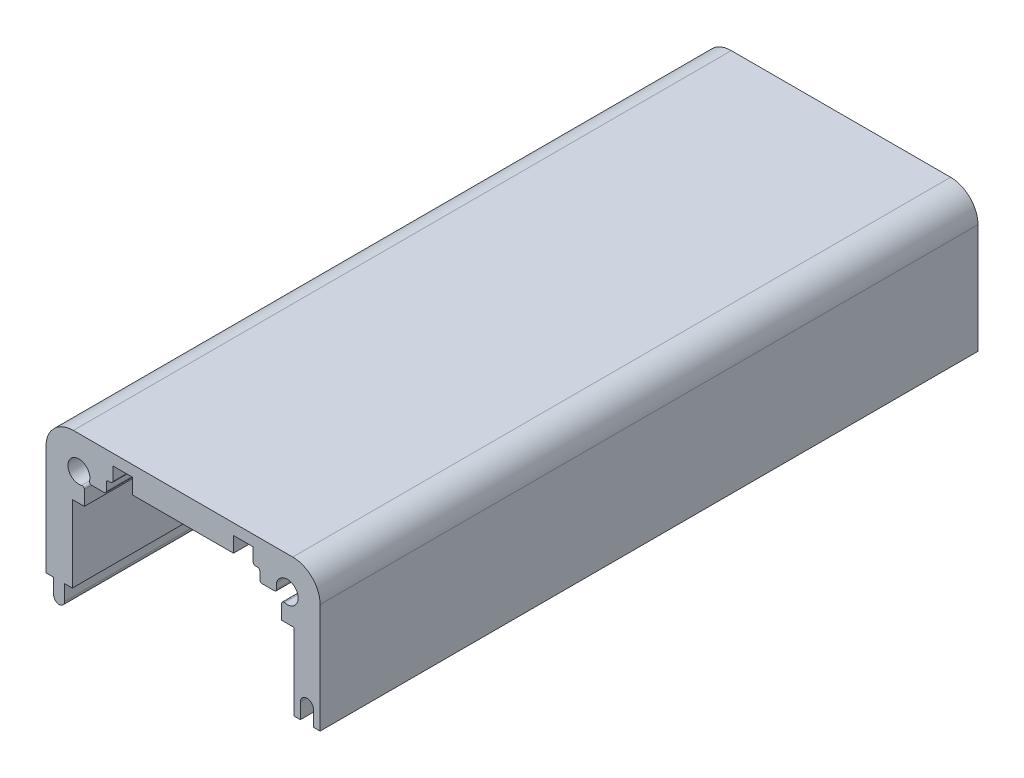
SolidWorks part; units mm, degrees
ref_plane "前视基准面" through (0, 0, 0) normal (0, 0, 1) x (1, 0, 0)
ref_plane "上视基准面" through (0, 0, 0) normal (0, 1, 0) x (1, 0, 0)
ref_plane "右视基准面" through (0, 0, 0) normal (1, 0, 0) x (0, 0, -1)
sketch "草图1" plane through (0, 0, 0) normal (0, 0, 1) x (1, 0, 0)
  line L0 (0, -173.8335) -> (0, 8517.8401) construction
  line L1 (-173.8335, 0) -> (8517.8401, 0) construction
  line L2 (-10, 0) -> (10, 0)
  line L3 (12.5, -2.5) -> (12.5, -12.5)
  line L4 (-4.6, -2.4) -> (4.6, -2.4)
  line L5 (4.6, -2.4) -> (4.6, -1)
  line L6 (4.6, -1) -> (6.4, -1)
  line L7 (6.4, -1) -> (6.4, -2.4)
  line L8 (6.4, -2.4) -> (7, -2.4)
  line L9 (7, -2.4) -> (7, -3.5)
  line L10 (7, -3.5) -> (8.634, -3.5)
  line L11 (12.5, -12.5) -> (11.9, -12.5)
  line L12 (9, -3.866) -> (9, -5.5)
  line L13 (9, -5.5) -> (10.1, -5.5)
  line L14 (10.1, -5.5) -> (10.1, -12.5)
  line L15 (10.7, -11.1) -> (10.7, -12.5)
  line L16 (11.9, -11.1) -> (11.9, -12.5)
  line L17 (10.7, -12.5) -> (10.1, -12.5)
  line L18 (-12.5, -2.5) -> (-12.5, -12.5)
  line L19 (-10.1, -5.5) -> (-10.1, -12.5)
  line L20 (-12.5, -12.5) -> (-11.8, -12.5)
  line L21 (-11.8, -13.9) -> (-11.8, -12.5)
  line L22 (-9, -5.5) -> (-10.1, -5.5)
  line L23 (-9, -3.866) -> (-9, -5.5)
  line L24 (-10.8, -13.9) -> (-10.8, -12.5)
  line L25 (-7, -3.5) -> (-8.634, -3.5)
  line L26 (-7, -2.4) -> (-7, -3.5)
  line L27 (-6.4, -2.4) -> (-7, -2.4)
  line L28 (-6.4, -1) -> (-6.4, -2.4)
  line L29 (-4.6, -1) -> (-6.4, -1)
  line L30 (-4.6, -2.4) -> (-4.6, -1)
  line L31 (-10.8, -12.5) -> (-10.1, -12.5)
  line L32 (-10.1, -12.5) -> (-12.5, -12.5) construction
  arc A0 (10, 0) -> (12.5, -2.5) centre (10, -2.5) cw
  arc A1 (9, -3.866) -> (8.5, -3) centre (9.5, -3) ccw
  arc A2 (8.5, -3) -> (8.634, -3.5) centre (9.5, -3) ccw
  arc A3 (11.9, -11.1) -> (10.7, -11.1) centre (11.3, -11.1) ccw
  arc A4 (-11.8, -13.9) -> (-10.8, -13.9) centre (-11.3, -13.9) ccw
  arc A5 (-8.5, -3) -> (-8.634, -3.5) centre (-9.5, -3) cw
  arc A6 (-9, -3.866) -> (-8.5, -3) centre (-9.5, -3) cw
  arc A7 (-10, 0) -> (-12.5, -2.5) centre (-10, -2.5) ccw
  point P9 (0, 0)
  point P26 (11.3, -10.5)
  point P52 (0, -2.4)
  point P53 (-11.3, -12.5)
  point P54 (-11.3, -14.4)
  dimension "D1" = 2.5
  dimension "D8" = 2
  dimension "D15" = 20.2
  dimension "D16" = 1.2
  dimension "D17" = 1
  dimension "D20" = 22.6
  dimension "D2" = 12.5
  dimension "D3" = 25
  dimension "D4" = 9.2
  dimension "D5" = 2.4
  dimension "D6" = 1
  dimension "D7" = 12.8
  dimension "D9" = 3
  dimension "D10" = 19
  dimension "D11" = 3.5
  dimension "D12" = 14
  dimension "D13" = 18
  dimension "D14" = 5.5
  dimension "D18" = 10.5
  dimension "D19" = 12.5
  dimension "D21" = 14.4
extrude "凸台-拉伸1" add sketch "草图1" along normal blind 60
fillet "圆角1" radius 0.2 10 edges at (-7, -2.4, 30) (-7, -3.5, 30) (-6.4, -2.4, 30) (7, -3.5, 30) (7, -2.4, 30) (6.4, -2.4, 30) (9, -3.866, 30) (8.634, -3.5, 30) (-9, -3.866, 30) (-8.634, -3.5, 30)
